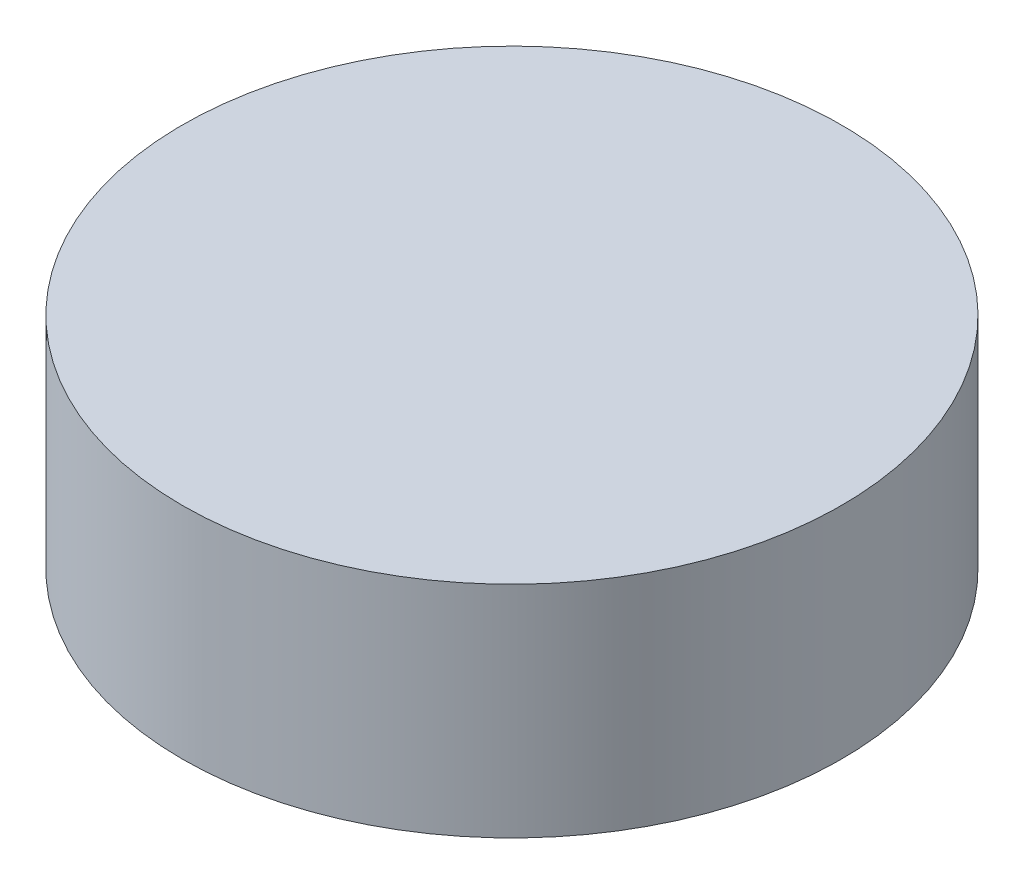
SolidWorks part; units mm, degrees
ref_plane "Front Plane" through (0, 0, 0) normal (0, 0, 1) x (1, 0, 0)
ref_plane "Top Plane" through (0, 0, 0) normal (0, 1, 0) x (1, 0, 0)
ref_plane "Right Plane" through (0, 0, 0) normal (1, 0, 0) x (0, 0, -1)
sketch "Sketch1" plane through (0, 0, 0) normal (0, 1, 0) x (1, 0, 0)
  circle A0 centre (0, 0) radius 15
  dimension "D1" = 30
extrude "Boss-Extrude1" add sketch "Sketch1" along normal blind 10
